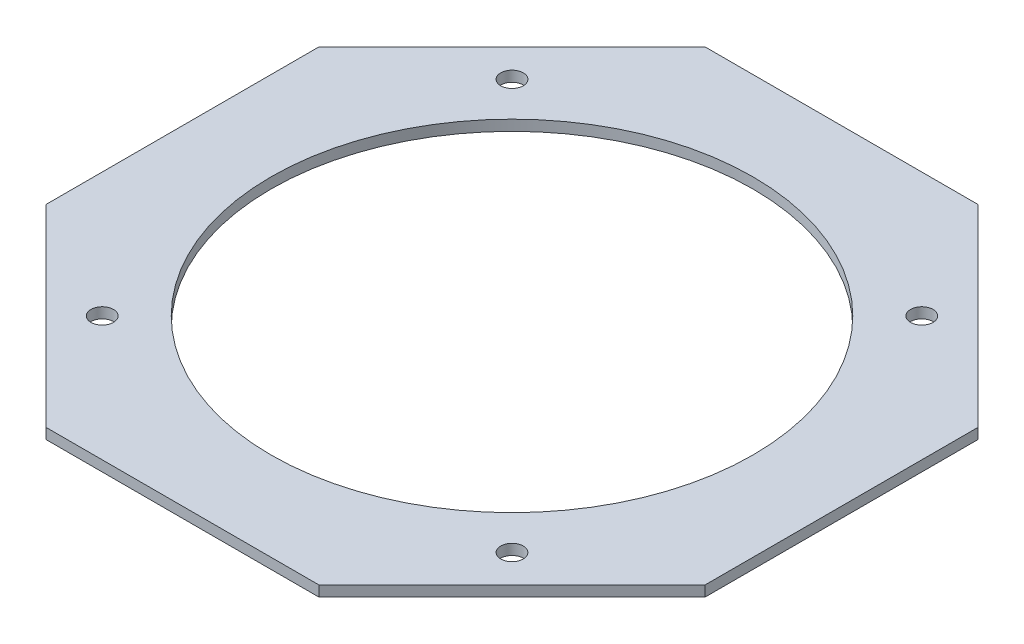
SolidWorks part; units mm, degrees
ref_plane "Front Plane" through (0, 0, 0) normal (0, 0, 1) x (1, 0, 0)
ref_plane "Top Plane" through (0, 0, 0) normal (0, 1, 0) x (1, 0, 0)
ref_plane "Right Plane" through (0, 0, 0) normal (1, 0, 0) x (0, 0, -1)
sketch "Sketch1" plane through (0, 0, 0) normal (0, 1, 0) x (1, 0, 0)
  line L1 (57.09, -23.6475) -> (57.09, 23.6475)
  line L2 (57.09, 23.6475) -> (23.6475, 57.09)
  line L3 (23.6475, 57.09) -> (-23.6475, 57.09)
  line L4 (-23.6475, 57.09) -> (-57.09, 23.6475)
  line L5 (-57.09, 23.6475) -> (-57.09, -23.6475)
  line L6 (-57.09, -23.6475) -> (-23.6475, -57.09)
  line L7 (-23.6475, -57.09) -> (23.6475, -57.09)
  line L8 (23.6475, -57.09) -> (57.09, -23.6475)
  circle A0 centre (0, 0) radius 57.09 construction
  dimension "D1" = 114.18
extrude "Boss-Extrude1" add sketch "Sketch1" along normal blind 1.83
sketch "Sketch2" plane through (0, 0, 0) normal (0, 1, 0) x (1, 0, 0)
  line L1 (35.5, 35.5) -> (-35.5, 35.5) construction
  line L2 (35.5, 35.5) -> (35.5, -35.5) construction
  line L3 (35.5, -35.5) -> (-35.5, -35.5) construction
  line L4 (-35.5, 35.5) -> (-35.5, -35.5) construction
  line L5 (35.5, 35.5) -> (-35.5, -35.5) construction
  line L6 (35.5, -35.5) -> (-35.5, 35.5) construction
  circle A0 centre (-35.5, 35.5) radius 1.95
  circle A1 centre (35.5, 35.5) radius 1.95
  circle A2 centre (35.5, -35.5) radius 1.95
  circle A3 centre (-35.5, -35.5) radius 1.95
  circle A4 centre (0, 0) radius 41.75
  point P0 (0, 0)
  dimension "D3" = 3.9
  dimension "D4" = 3.9
  dimension "D5" = 3.9
  dimension "D6" = 3.9
  dimension "D7" = 83.5
  dimension "D1" = 71
  dimension "D2" = 71
extrude "Cut-Extrude1" cut sketch "Sketch2" along normal blind 23.83
